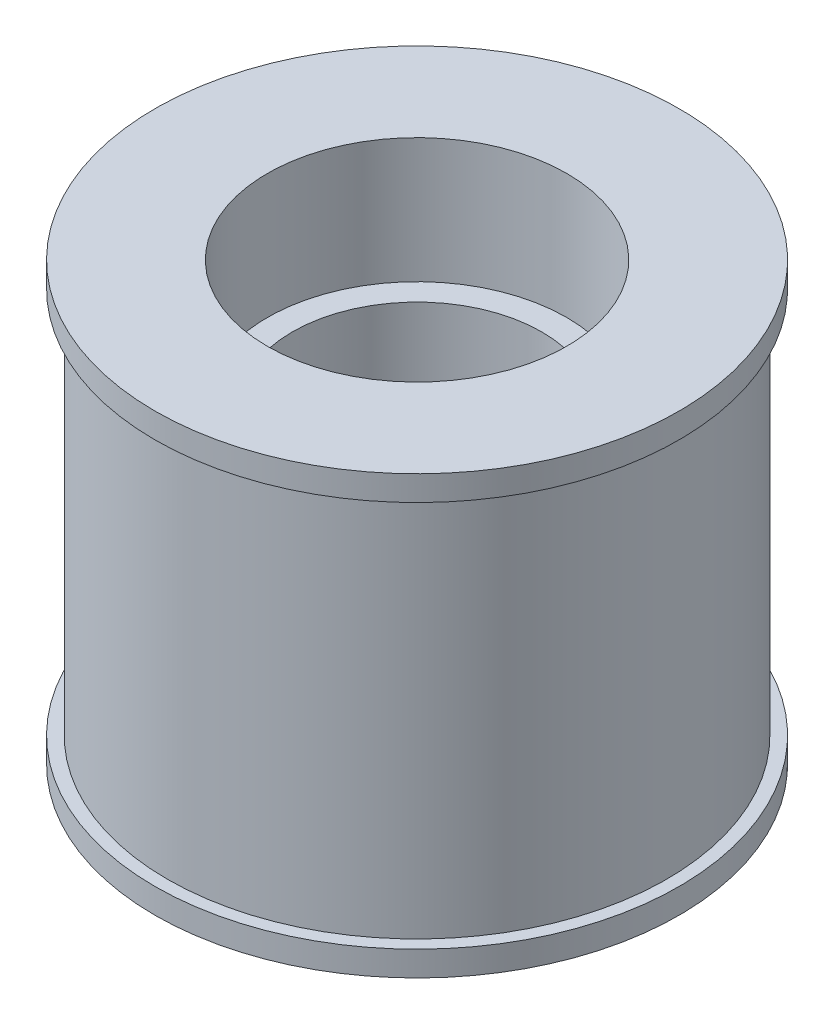
SolidWorks part; units mm, degrees
ref_plane "前视基准面" through (0, 0, 0) normal (0, 0, 1) x (1, 0, 0)
ref_plane "上视基准面" through (0, 0, 0) normal (0, 1, 0) x (1, 0, 0)
ref_plane "右视基准面" through (0, 0, 0) normal (1, 0, 0) x (0, 0, -1)
sketch "草图1" plane through (0, 0, 0) normal (0, 1, 0) x (1, 0, 0)
  circle A0 centre (0, 0) radius 21
  dimension "D1" = 42
extrude "凸台-拉伸1" add sketch "草图1" along normal mid plane 35
sketch "草图2" plane through (0, 0, 0) normal (0, 0, 1) x (1, 0, 0)
  line L0 (21, 15.5) -> (20, 15.5)
  line L1 (20, 15.5) -> (20, -15.5)
  line L2 (20, -15.5) -> (21, -15.5)
  line L3 (21, -15.5) -> (21, 15.5)
  line L4 (21, 17.5) -> (-21, 17.5) construction
  line L5 (-21, -17.5) -> (21, -17.5) construction
  dimension "D1" = 1
  dimension "D2" = 2
  dimension "D3" = 20
  dimension "D4" = 2
revolve "切除-旋转1" cut sketch "草图2" angle 360 about axis through (0, 17.5, 0) along (0, -1, 0)
sketch "草图3" plane through (0, 17.5, 0) normal (0, 1, 0) x (1, 0, 0)
  circle A0 centre (0, 0) radius 12
  dimension "D1" = 24
extrude "切除-拉伸1" cut sketch "草图3" against normal blind 10
sketch "草图15" plane through (0, 7.5, 0) normal (0, 1, 0) x (1, 0, 0)
  circle A0 centre (0, 0) radius 10
  dimension "D1" = 20
extrude "切除-拉伸3" cut sketch "草图15" against normal through all
mirror "镜向1" about plane through (0, 0, 0) normal (0, 1, 0) of "切除-拉伸1"
scale "Scale1" scale about centroid uniform scaling yes scale factor 2
